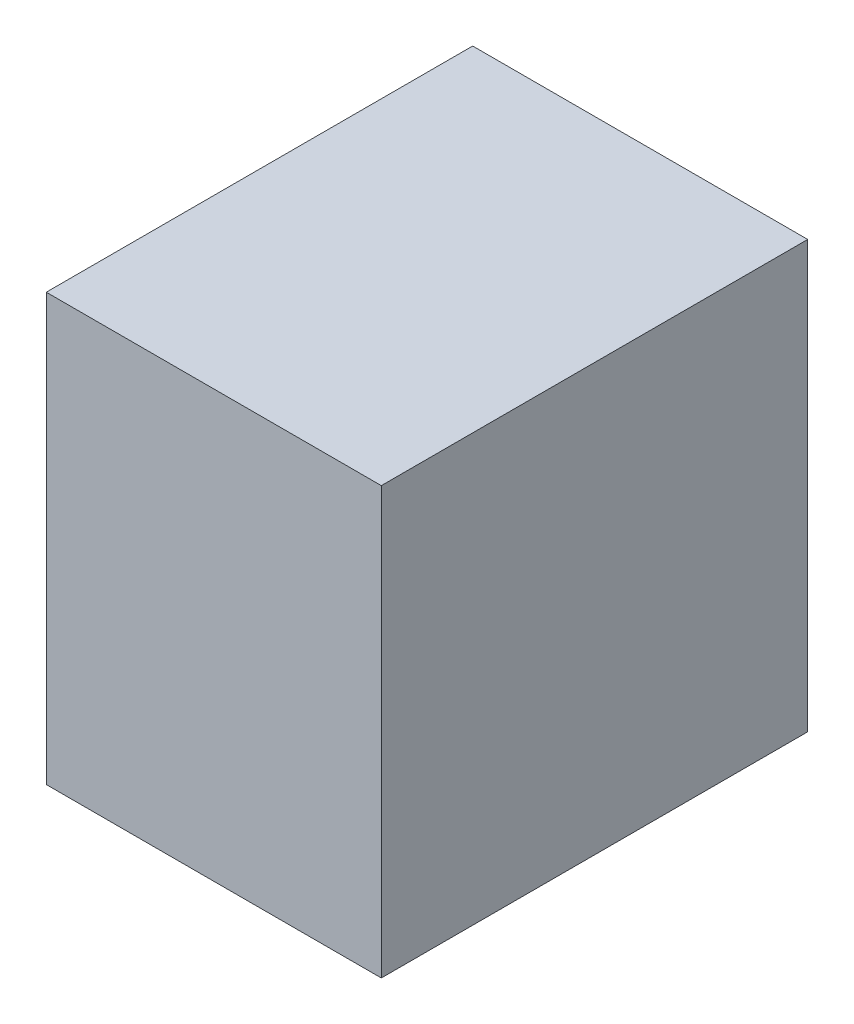
SolidWorks part; units mm, degrees
ref_plane "前视基准面" through (0, 0, 0) normal (0, 0, 1) x (1, 0, 0)
ref_plane "上视基准面" through (0, 0, 0) normal (0, 1, 0) x (1, 0, 0)
ref_plane "右视基准面" through (0, 0, 0) normal (1, 0, 0) x (0, 0, -1)
sketch "草图1" plane through (0, 0, 0) normal (0, 1, 0) x (1, 0, 0)
  line L1 (-9.7778, 3.9149) -> (-4.2778, 3.9149)
  line L2 (-9.7778, 3.9149) -> (-9.7778, -3.0851)
  line L3 (-9.7778, -3.0851) -> (-4.2778, -3.0851)
  line L4 (-4.2778, 3.9149) -> (-4.2778, -3.0851)
  dimension "D1" = 5.5
  dimension "D2" = 7
extrude "凸台-拉伸1" add sketch "草图1" along normal blind 7
